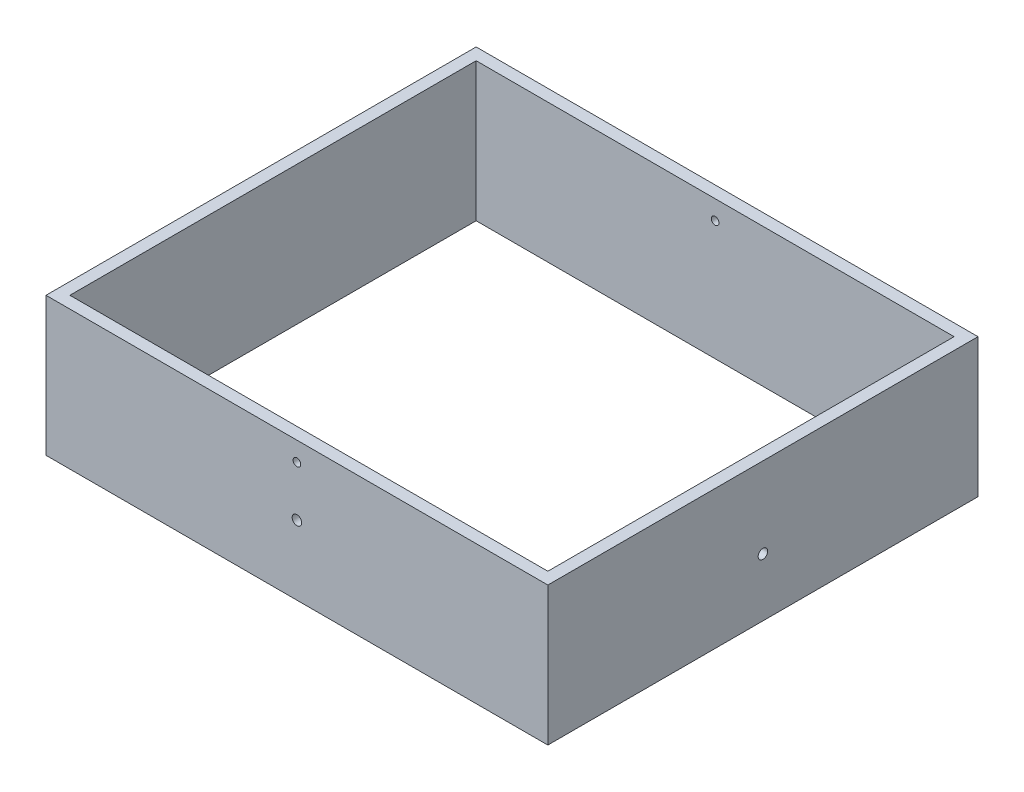
SolidWorks part; units mm, degrees
ref_plane "Front Plane" through (0, 0, 0) normal (0, 0, 1) x (1, 0, 0)
ref_plane "Top Plane" through (0, 0, 0) normal (0, 1, 0) x (1, 0, 0)
ref_plane "Right Plane" through (0, 0, 0) normal (1, 0, 0) x (0, 0, -1)
sketch "Sketch1" plane through (0, 0, 0) normal (0, 1, 0) x (1, 0, 0)
  line L1 (-118.9999, 72.9694) -> (214.3751, 72.9694)
  line L2 (-118.9999, 72.9694) -> (-118.9999, -212.7806)
  line L3 (-118.9999, -212.7806) -> (214.3751, -212.7806)
  line L4 (214.3751, 72.9694) -> (214.3751, -212.7806)
  line L5 (-111.0624, 65.0319) -> (206.4376, 65.0319)
  line L6 (-111.0624, 65.0319) -> (-111.0624, -204.8431)
  line L7 (-111.0624, -204.8431) -> (206.4376, -204.8431)
  line L8 (206.4376, 65.0319) -> (206.4376, -204.8431)
  dimension "D1" = 333.375
  dimension "D2" = 285.75
  dimension "D3" = 7.9375
  dimension "D4" = 7.9375
  dimension "D5" = 7.9375
  dimension "D6" = 7.9375
extrude "Boss-Extrude1" add sketch "Sketch1" along normal blind 92.075
sketch "Sketch2" plane through (0, 0, 212.7806) normal (0, 0, 1) x (1, 0, 0)
  line L0 (47.6876, 0) -> (47.6876, 79.375) construction
  line L1 (-118.9999, 0) -> (214.3751, 0) construction
  circle A0 centre (47.6876, 79.375) radius 2.54
  dimension "D1" = 79.375
extrude "Cut-Extrude1" cut sketch "Sketch2" against normal through all
sketch "Sketch3" plane through (0, 0, 212.7806) normal (0, 0, 1) x (1, 0, 0)
  line L0 (-118.9999, 46.0375) -> (214.3751, 46.0375) construction
  line L1 (-118.9999, 92.075) -> (-118.9999, 0) construction
  line L2 (214.3751, 92.075) -> (214.3751, 0) construction
  circle A0 centre (47.6876, 46.0375) radius 3.175
  dimension "D1" = 6.35
extrude "Cut-Extrude2" cut sketch "Sketch3" against normal up to surface (7.9375 mm away) up to face at (45.1476, 79.375, 204.8431)
sketch "Sketch4" plane through (214.3751, 0, 0) normal (1, 0, 0) x (0, 0, -1)
  line L0 (-212.7806, 38.5596) -> (72.9694, 38.5596) construction
  line L1 (-212.7806, 92.075) -> (-212.7806, 0) construction
  line L2 (72.9694, 92.075) -> (72.9694, 0) construction
  circle A0 centre (-69.9056, 38.5596) radius 3.175
  dimension "D1" = 6.35
extrude "Cut-Extrude3" cut sketch "Sketch4" against normal up to surface (7.9375 mm away) up to face at (206.4376, 46.0375, 69.9056)
